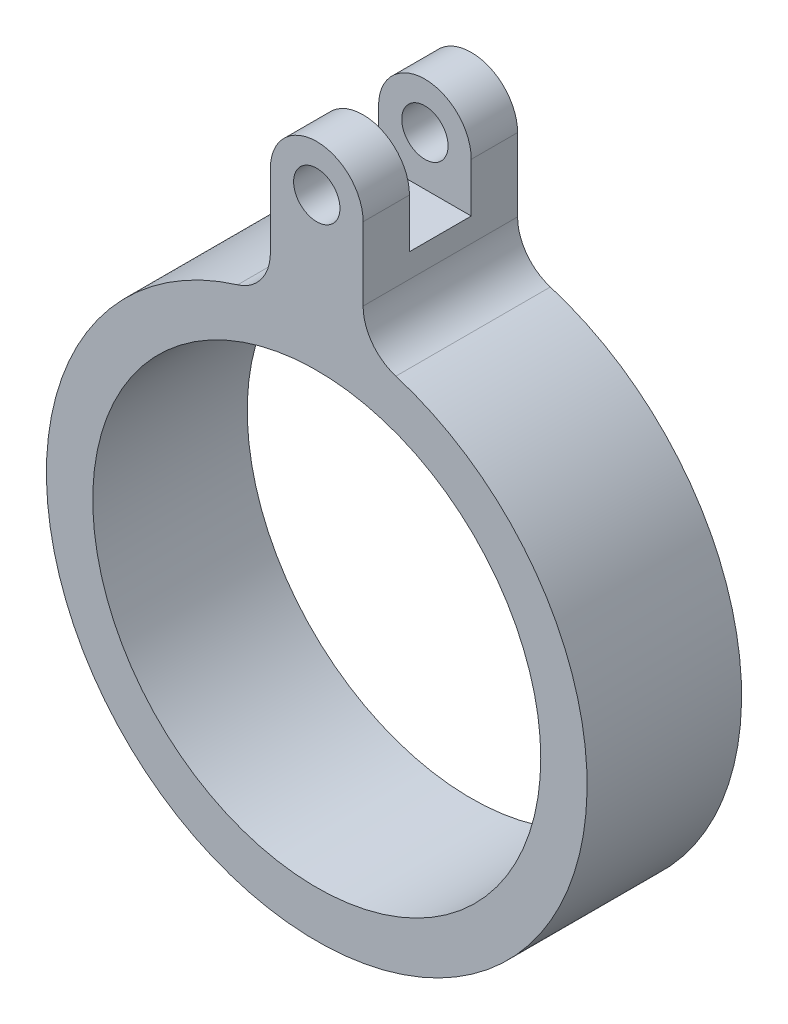
SolidWorks part; units mm, degrees
ref_plane "Front Plane" through (0, 0, 0) normal (0, 0, 1) x (1, 0, 0)
ref_plane "Top Plane" through (0, 0, 0) normal (0, 1, 0) x (1, 0, 0)
ref_plane "Right Plane" through (0, 0, 0) normal (1, 0, 0) x (0, 0, -1)
sketch "Sketch1" plane through (0, 0, 0) normal (0, 0, 1) x (1, 0, 0)
  circle A0 centre (0, 0) radius 14.5
  circle A1 centre (0, 0) radius 17.5
extrude "Boss-Extrude1" add sketch "Sketch1" along normal blind 10
sketch "Sketch4" plane through (0, 0, 10) normal (0, 0, 1) x (1, 0, 0)
  line L1 (-3, 19.2508) -> (-3, 16.4304)
  line L2 (3, 24.3279) -> (3, 19.2508)
  line L3 (-3, 24.3279) -> (-3, 19.2508)
  line L4 (-3, 24.3279) -> (3, 24.3279)
  line L5 (-3, 16.4304) -> (3, 16.4304)
  line L6 (3, 16.4304) -> (3, 19.2508)
extrude "Boss-Extrude2" add sketch "Sketch4" against normal blind 10
sketch "Sketch5" plane through (0, 0, 10) normal (0, 0, 1) x (1, 0, 0)
  line L0 (3, 24.3279) -> (-3, 24.3279) construction
  circle A0 centre (0, 24.3279) radius 3
extrude "Boss-Extrude3" add sketch "Sketch5" against normal blind 10
fillet "Fillet1" radius 3 2 edges at (-3, 17.2409, 5) (3, 17.2409, 5)
sketch "Sketch6" plane through (0, 0, 10) normal (0, 0, 1) x (1, 0, 0)
  circle A0 centre (0, 24.3279) radius 1.5
extrude "Cut-Extrude1" cut sketch "Sketch6" against normal blind 10
ref_plane "Plane2" through (0, 0, 7) normal (0, 0, 1) x (1, 0, 0)
sketch "Sketch7" plane through (0, 0, 7) normal (0, 0, 1) x (1, 0, 0)
  line L0 (3.4291, 21.1484) -> (-6, 21.1484)
  line L2 (3.4291, 21.1484) -> (5.0673, 21.1484)
  line L4 (-6, 21.1484) -> (-6, 28.2637)
  line L5 (-6, 28.2637) -> (5.3199, 28.2637)
  line L6 (5.3199, 28.2637) -> (5.3199, 21.3279)
  line L7 (5.3199, 21.3279) -> (5.0673, 21.1484)
  arc A1 (3, 19.6023) -> (5.122, 16.7337) centre (6, 19.6023) ccw construction
extrude "Cut-Extrude2" cut sketch "Sketch7" against normal blind 4
